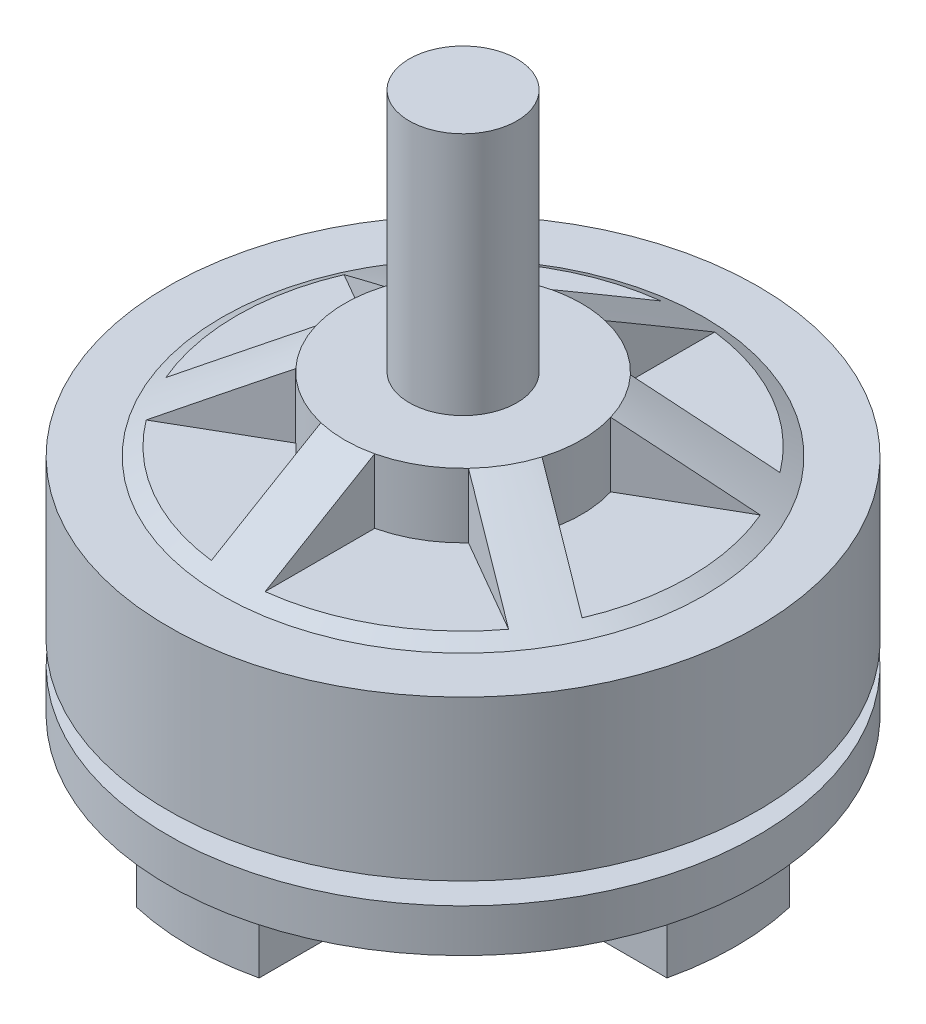
SolidWorks part; units mm, degrees
ref_plane "Alzado" through (0, 0, 0) normal (0, 0, 1) x (1, 0, 0)
ref_plane "Planta" through (0, 0, 0) normal (0, 1, 0) x (1, 0, 0)
ref_plane "Vista lateral" through (0, 0, 0) normal (1, 0, 0) x (0, 0, -1)
sketch "Croquis1" plane through (0, 0, 0) normal (0, 0, 1) x (1, 0, 0)
  line L0 (0, 0) -> (0, 55.0883) construction
  line L1 (0, 0) -> (-12.65, 0)
  line L2 (-12.65, 0) -> (-12.65, 3)
  line L3 (0, 28.1473) -> (0, 6)
  line L4 (0, 5) -> (0, 0)
  line L5 (-12.65, 3) -> (-13.7, 3)
  line L6 (-13.7, 3) -> (-13.7, 5)
  line L7 (-13.7, 5) -> (0, 5)
  line L9 (0, 6) -> (-13.7, 6)
  line L10 (-13.7, 6) -> (-13.7, 13.4)
  line L11 (-13.7, 13.4) -> (-11.2, 13.4)
  line L12 (-11.2, 13.4) -> (-5.5, 16.8073)
  line L13 (-5.5, 16.8073) -> (-2.5, 16.8073)
  line L14 (-2.5, 16.8073) -> (-2.5, 28.1473)
  line L15 (-2.5, 28.1473) -> (0, 28.1473)
  dimension "D1" = 27.4
  dimension "D2" = 5
  dimension "D3" = 11
  dimension "D4" = 25.3
  dimension "D5" = 27.4
  dimension "D6" = 1
  dimension "D7" = 3
  dimension "D8" = 5
  dimension "D9" = 13.4
  dimension "D10" = 16.8073
  dimension "D11" = 11.34
  dimension "D12" = 2.5
revolve "Revolución1" add sketch "Croquis1" angle 360 about L0
sketch "Croquis2" plane through (0, 0, 0) normal (0, -1, 0) x (1, 0, 0)
  line L0 (0, -12.65) -> (0, 12.65) construction
  line L1 (-12.65, 0) -> (12.65, 0) construction
  line L2 (-7.85, -2.85) -> (-12.3248, -2.85)
  line L4 (2.85, -12.3248) -> (2.85, -7.85)
  line L6 (-2.85, -12.3248) -> (-2.85, -7.85)
  line L7 (2.85, 7.85) -> (2.85, 12.3248)
  line L8 (-2.85, 7.85) -> (-2.85, 12.3248)
  line L9 (12.3248, -2.85) -> (7.85, -2.85)
  line L11 (12.3248, 2.85) -> (7.85, 2.85)
  line L13 (-7.85, 2.85) -> (-12.3248, 2.85)
  circle A0 centre (0, 0) radius 12.65 construction
  circle A1 centre (0, 0) radius 12.65 construction
  arc A2 (12.3248, -2.85) -> (12.3321, 2.8181) centre (0, 0) ccw
  circle A3 centre (0, 0) radius 12.65
  arc A4 (-12.3248, 2.85) -> (-12.3248, -2.85) centre (0, 0) ccw
  arc A5 (2.85, 12.3248) -> (-2.85, 12.3248) centre (0, 0) ccw
  arc A6 (12.3248, -2.85) -> (12.3248, 2.85) centre (0, 0) ccw
  arc A7 (-2.85, -12.3248) -> (2.85, -12.3248) centre (0, 0) ccw
  arc A8 (-2.85, 7.85) -> (-7.85, 2.85) centre (-7.85, 7.85) cw
  arc A9 (7.85, 2.85) -> (2.85, 7.85) centre (7.85, 7.85) cw
  arc A10 (2.85, -7.85) -> (7.85, -2.85) centre (7.85, -7.85) cw
  arc A11 (-2.85, -7.85) -> (-7.85, -2.85) centre (-7.85, -7.85) ccw
  circle A12 centre (0, 0) radius 3.75
  circle A13 centre (0, 7.9) radius 1.25
  circle A14 centre (0, -7.9) radius 1.25
  circle A15 centre (-7.9, 0) radius 1.25
  circle A16 centre (7.9, 0) radius 1.25
  point P25 (-2.85, 2.85)
  point P42 (-6.65, 0)
  point P43 (0, 6.65)
  circle M20 centre (0, 0) radius 12.65
  dimension "D6" = 5
  dimension "D7" = 7.5
  dimension "D8" = 2.5
  dimension "D2" = 5.7
  dimension "D3" = 5.7
  dimension "D4" = 2.85
  dimension "D5" = 2.85
  dimension "D9" = 6
  dimension "D10" = 6
  dimension "D1" = 0
extrude "Cortar-Extruir1" cut sketch "Croquis2" against normal blind 3 contours L6 A11 L2 M20 | A8 L8 L13 M20 | A9 L11 L7 M20 | A10 L4 L9 M20 | A12 | A14 | A16 | A13 | A15
sketch "Croquis3" plane through (0, 16.8073, 0) normal (0, 1, 0) x (1, 0, 0)
  line L0 (0, -11.2) -> (0, 11.2) construction
  line L1 (9.6995, 5.6) -> (-9.6995, -5.6) construction
  line L2 (-9.6995, 5.6) -> (9.6995, -5.6) construction
  line L3 (-9.0139, 6.6475) -> (10.2639, -4.4825)
  line L5 (9.0139, -6.6475) -> (-10.2639, 4.4825)
  line L7 (-9.0139, -6.6475) -> (10.2639, 4.4825)
  line L9 (9.0139, 6.6475) -> (-10.2639, -4.4825)
  line L12 (1.25, 11.13) -> (1.25, -11.13)
  line L14 (-1.25, -11.13) -> (-1.25, 11.13)
  circle A0 centre (0, 0) radius 11.2 construction
  arc A6 (-9.7032, -5.5936) -> (-9.6995, -5.6) centre (0, 0) ccw
  arc A7 (-10.2639, 4.4825) -> (-10.2639, -4.4825) centre (0, 0) ccw
  arc A8 (-1.25, 11.13) -> (-9.0139, 6.6475) centre (0, 0) ccw
  arc A9 (9.0139, 6.6475) -> (1.25, 11.13) centre (0, 0) ccw
  arc A10 (10.2639, -4.4825) -> (10.2639, 4.4825) centre (0, 0) ccw
  arc A11 (-9.0139, -6.6475) -> (-1.25, -11.13) centre (0, 0) ccw
  arc A12 (-9.7032, -5.5936) -> (-9.6995, -5.6) centre (0, 0) ccw
  arc A13 (1.25, -11.13) -> (9.0139, -6.6475) centre (0, 0) ccw
  circle M16 centre (0, 0) radius 5.5
  dimension "D1" = 60
  dimension "D2" = 60
  dimension "D3" = 1.25
  dimension "D4" = 2.5
  dimension "D5" = 1.25
  dimension "D6" = 2.5
  dimension "D7" = 1.25
  dimension "D8" = 2.5
extrude "Cortar-Extruir2" cut sketch "Croquis3" against normal blind 3 contours L5 A7 L9 M16 | L14 A8 L3 M16 | L9 A9 L12 M16 | L3 A10 L7 M16 | L12 A13 L5 M16 | L7 A11 L14 M16
